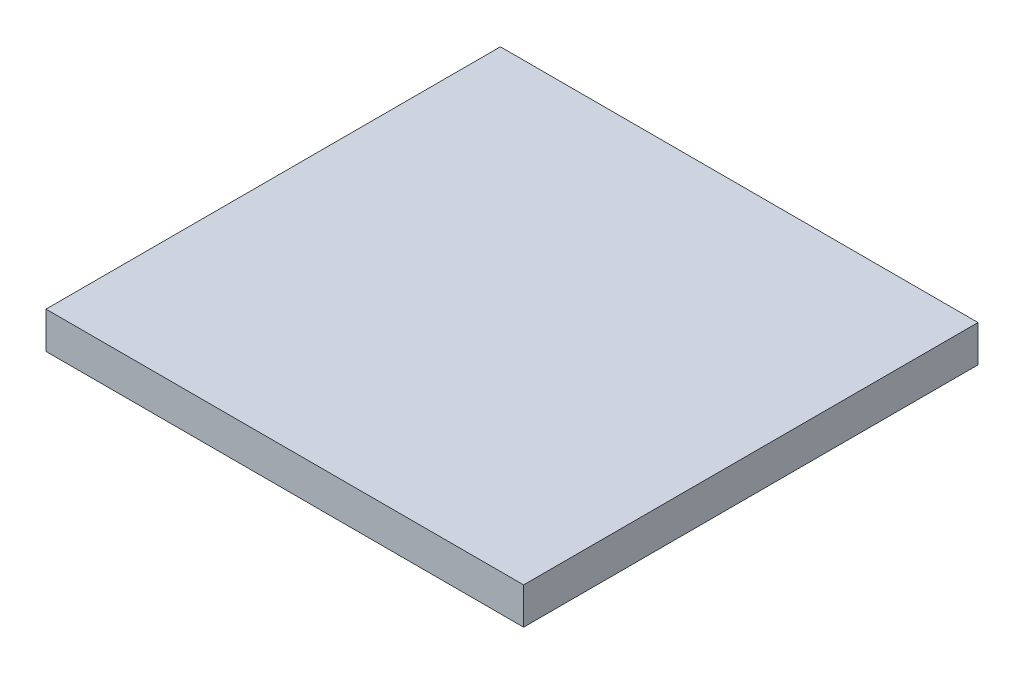
SolidWorks part; units mm, degrees
ref_plane "Front Plane" through (0, 0, 0) normal (0, 0, 1) x (1, 0, 0)
ref_plane "Top Plane" through (0, 0, 0) normal (0, 1, 0) x (1, 0, 0)
ref_plane "Right Plane" through (0, 0, 0) normal (1, 0, 0) x (0, 0, -1)
sketch "Sketch1" plane through (0, 0, 0) normal (0, 1, 0) x (1, 0, 0)
  line L1 (-19.535, 18.585) -> (19.535, 18.585)
  line L2 (-19.535, 18.585) -> (-19.535, -18.585)
  line L3 (-19.535, -18.585) -> (19.535, -18.585)
  line L4 (19.535, 18.585) -> (19.535, -18.585)
  line L5 (-19.535, 18.585) -> (19.535, -18.585) construction
  line L6 (-19.535, -18.585) -> (19.535, 18.585) construction
  point P0 (0, 0)
  dimension "D1" = 39.07
  dimension "D2" = 37.17
extrude "Boss-Extrude1" add sketch "Sketch1" along normal blind 3
